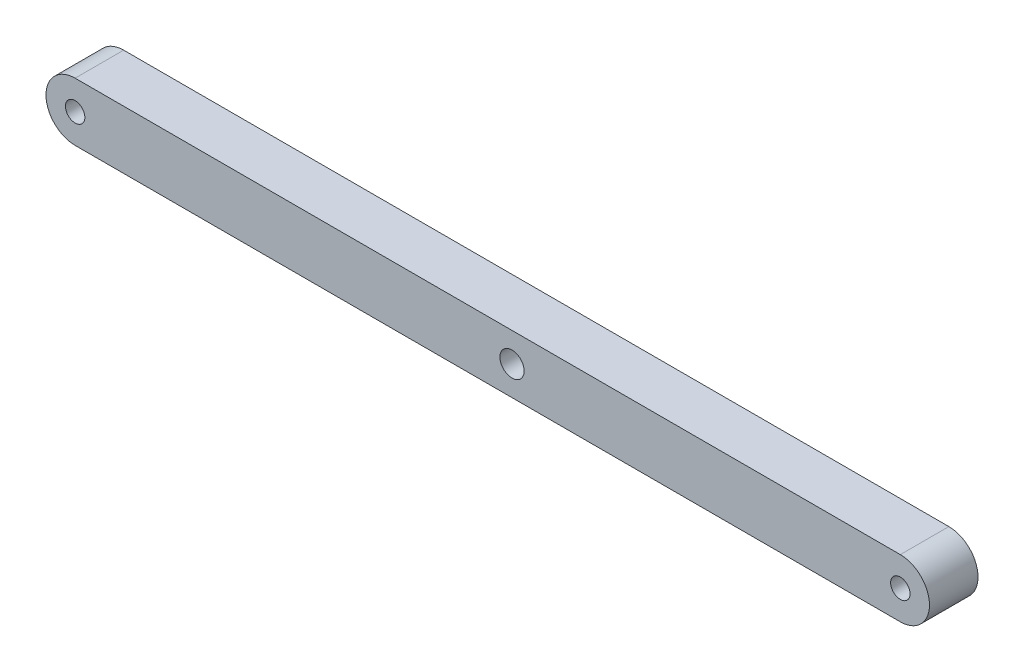
SolidWorks part; units mm, degrees
ref_plane "Front Plane" through (0, 0, 0) normal (0, 0, 1) x (1, 0, 0)
ref_plane "Top Plane" through (0, 0, 0) normal (0, 1, 0) x (1, 0, 0)
ref_plane "Right Plane" through (0, 0, 0) normal (1, 0, 0) x (0, 0, -1)
sketch "Sketch1" plane through (0, 0, 0) normal (0, 0, 1) x (1, 0, 0)
  line L0 (0, 0) -> (85, 0) construction
  line L1 (0, 3) -> (85, 3)
  line L2 (85, -3) -> (0, -3)
  arc A0 (0, 3) -> (0, -3) centre (0, 0) ccw
  circle A2 centre (0, 0) radius 1
  arc A3 (85, -3) -> (85, 3) centre (85, 0) ccw
  circle A4 centre (85, 0) radius 1
  circle A5 centre (0, 0) radius 3 construction
  circle A6 centre (45, 0) radius 1.25
  point P16 (39.2579, 0)
  dimension "D1" = 6
  dimension "D3" = 2
  dimension "D5" = 2.5
  dimension "D4" = 85
  dimension "D6" = 45
  dimension "D2" = 2
extrude "Boss-Extrude1" add sketch "Sketch1" along normal blind 5
